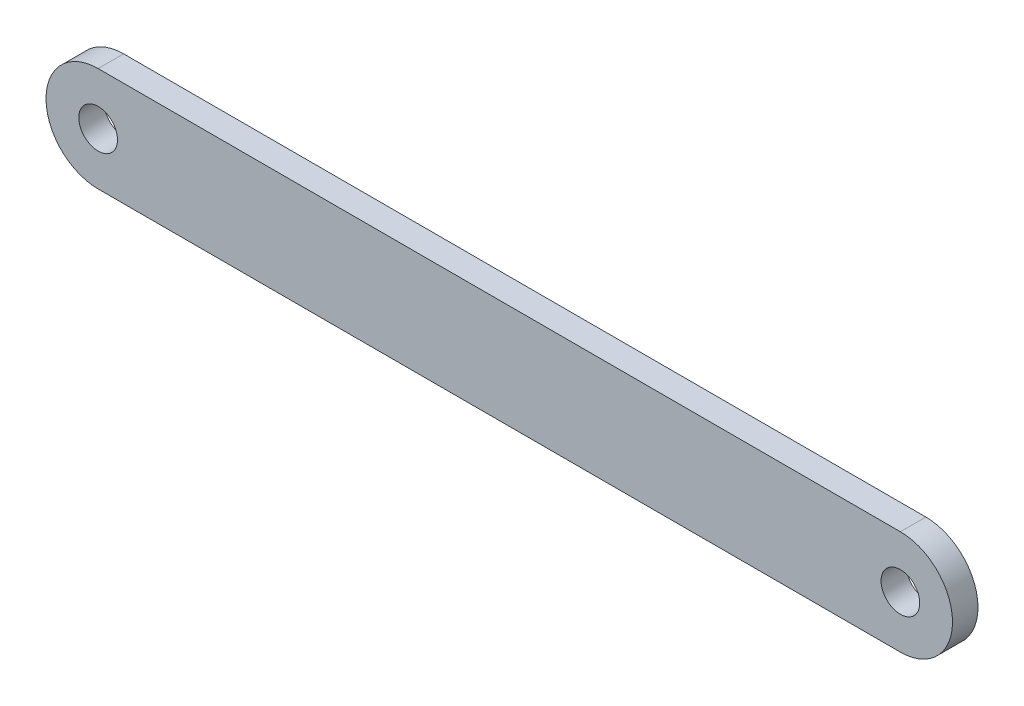
SolidWorks part; units mm, degrees
material "6061 Alloy"
ref_plane "Front Plane" through (0, 0, 0) normal (0, 0, 1) x (1, 0, 0)
ref_plane "Top Plane" through (0, 0, 0) normal (0, 1, 0) x (1, 0, 0)
ref_plane "Right Plane" through (0, 0, 0) normal (1, 0, 0) x (0, 0, -1)
sketch "Sketch1" plane through (0, 0, 0) normal (0, 0, 1) x (1, 0, 0)
  line L0 (-50, 0) -> (50, 0) construction
  line L1 (-50, 6.5) -> (50, 6.5)
  line L2 (-50, -6.5) -> (50, -6.5)
  arc A0 (-50, 6.5) -> (-50, -6.5) centre (-50, 0) ccw
  arc A1 (50, -6.5) -> (50, 6.5) centre (50, 0) ccw
  circle A2 centre (-50, 0) radius 2.413
  circle A3 centre (50, 0) radius 2.413
  point P2 (0, 0)
  dimension "D1" = 4.826
  dimension "D2" = 100
  dimension "D3" = 13
extrude "Boss-Extrude1" add sketch "Sketch1" along normal blind 3.175
